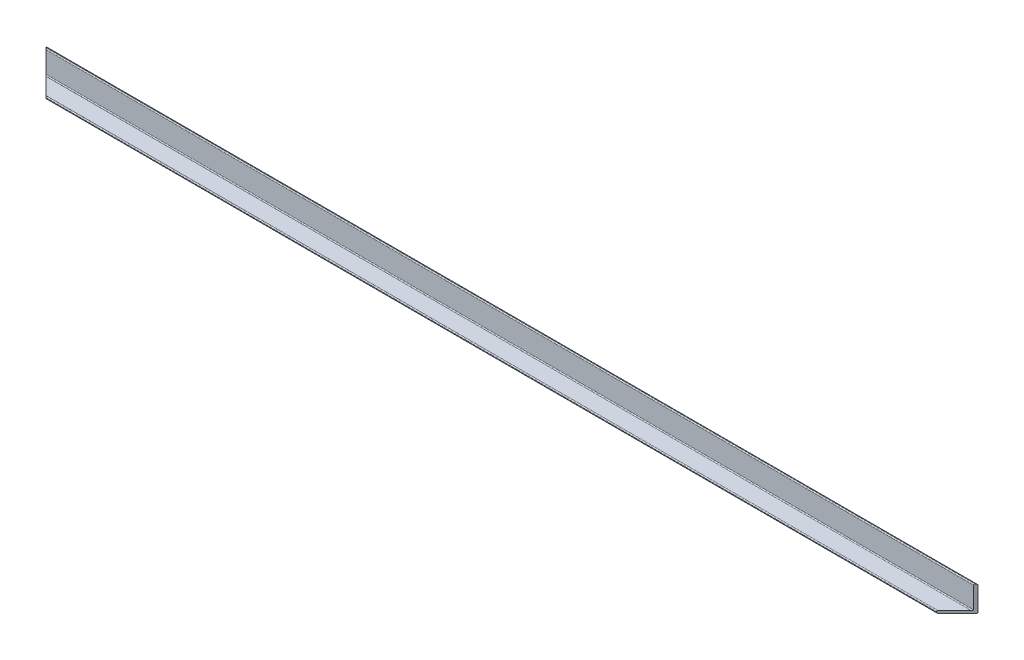
SolidWorks part; units mm, degrees
ref_plane "Front Plane" through (0, 0, 0) normal (0, 0, 1) x (1, 0, 0)
ref_plane "Top Plane" through (0, 0, 0) normal (0, 1, 0) x (1, 0, 0)
ref_plane "Right Plane" through (0, 0, 0) normal (1, 0, 0) x (0, 0, -1)
sketch "Sketch1" plane through (0, 0, 0) normal (0, 1, 0) x (1, 0, 0)
  line L1 (-505, 11.25) -> (505, 11.25)
  line L2 (-505, 11.25) -> (-505, -11.25)
  line L3 (-505, -11.25) -> (505, -11.25)
  line L4 (505, 11.25) -> (505, -11.25)
  line L5 (-505, 11.25) -> (505, -11.25) construction
  line L6 (-505, -11.25) -> (505, 11.25) construction
  point P0 (0, 0)
  dimension "D1" = 1010
  dimension "D2" = 22.5
extrude "Boss-Extrude1" add sketch "Sketch1" along normal blind 2.5
sketch "Sketch2" plane through (0, 2.5, 0) normal (0, 1, 0) x (1, 0, 0)
  line L0 (505, -11.25) -> (505, 11.25) construction
  line L1 (-505, 11.25) -> (505, 11.25)
  line L2 (-505, 11.25) -> (-505, 8.75)
  line L3 (-505, 8.75) -> (505, 8.75)
  line L4 (505, 11.25) -> (505, 8.75)
  dimension "D1" = 2.5
extrude "Boss-Extrude2" add sketch "Sketch2" along normal blind 25
sketch "Sketch3" plane through (0, 0, 0) normal (0, -1, 0) x (-1, 0, 0)
  line L0 (505, 11.25) -> (505, -11.25)
  line L1 (505, 11.25) -> (482.5, -11.25)
  line L3 (482.5, -11.25) -> (505, -11.25)
  line L4 (-505, 11.25) -> (-505, -11.25)
  line L5 (-505, -11.25) -> (-482.5, -11.25)
  line L6 (505, -11.25) -> (-505, -11.25) construction
  line L7 (-482.5, -11.25) -> (-505, 11.25)
  dimension "D1" = 45
  dimension "D2" = 45
extrude "Cut-Extrude1" cut sketch "Sketch3" against normal through all
fillet "Fillet1" radius 1 6 edges at (0, 27.5, -8.75) (0, 27.5, -11.25) (0, 2.5, 11.25) (0, 0, 11.25) (0, 0, -11.25) (0, 2.5, -8.75)
